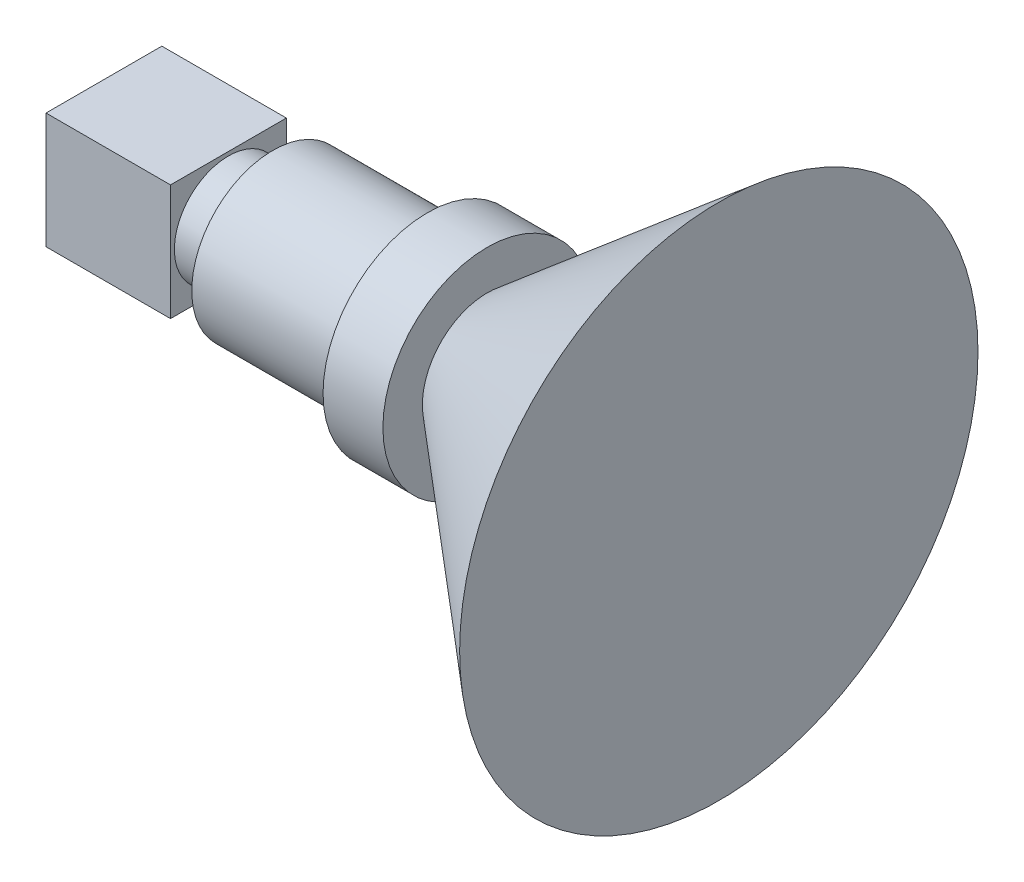
SolidWorks part; units mm, degrees
ref_plane "Front Plane" through (0, 0, 0) normal (0, 0, 1) x (1, 0, 0)
ref_plane "Top Plane" through (0, 0, 0) normal (0, 1, 0) x (1, 0, 0)
ref_plane "Right Plane" through (0, 0, 0) normal (1, 0, 0) x (0, 0, -1)
sketch "Sketch2" plane through (0, 0, 0) normal (0, 1, 0) x (1, 0, 0)
  line L1 (-16.125, -15) -> (16.125, -15)
  line L2 (-16.125, -15) -> (-16.125, 15)
  line L3 (-16.125, 15) -> (16.125, 15)
  line L4 (16.125, -15) -> (16.125, 15)
  line L5 (-16.125, -15) -> (16.125, 15) construction
  line L6 (-16.125, 15) -> (16.125, -15) construction
  point P0 (0, 0)
  dimension "D1" = 32.25
  dimension "D2" = 30
extrude "Boss-Extrude1" add sketch "Sketch2" along normal mid plane 30
sketch "Sketch4" plane through (16.125, 0, 0) normal (1, 0, 0) x (0, 0, -1)
  circle A0 centre (0, 0) radius 14
  dimension "D1" = 28
extrude "Boss-Extrude2" add sketch "Sketch4" along normal blind 11.5
sketch "Sketch5" plane through (27.625, 0, 0) normal (1, 0, 0) x (0, 0, -1)
  circle A0 centre (0, 0) radius 21
  dimension "D1" = 42
extrude "Boss-Extrude3" add sketch "Sketch5" along normal blind 40
sketch "Sketch6" plane through (67.625, 0, 0) normal (1, 0, 0) x (0, 0, -1)
  circle A0 centre (0, 0) radius 27
  dimension "D1" = 54
extrude "Boss-Extrude4" add sketch "Sketch6" along normal blind 15.5
sketch "Sketch12" plane through (0, 0, 0) normal (0, 0, 1) x (1, 0, 0)
  line L0 (63.125, 0) -> (143.125, 67.128)
  line L2 (143.125, 67.128) -> (143.125, -67.128) construction
  line L3 (143.125, -67.128) -> (63.125, 0) construction
  line L4 (63.125, 0) -> (143.125, 0) construction
  line L5 (83.125, -27) -> (83.125, 27) construction
  line L6 (63.125, 0) -> (143.125, 0)
  line L7 (143.125, 0) -> (143.125, 67.128)
  dimension "D1" = 80
  dimension "D2" = 20
  dimension "D3" = 80
revolve "Revolve1" add sketch "Sketch12" angle 360 about L6
sketch "Sketch13" plane through (0, -15, 0) normal (0, -1, 0) x (1, 0, 0)
  line L0 (-16.125, 0) -> (-12.125, 0) construction
  line L1 (-16.125, -15) -> (-16.125, 15) construction
  dimension "D1" = 4
hole_wizard "Tap Drill for 1/4-20 Tap1" positions "Sketch14" profile "Sketch15" hole size "1/4-20" standard "ANSI Inch"
sketch "Sketch14" plane through (0, -15, 0) normal (0, -1, 0) x (-1, 0, 0)
  point P0 (12.125, 0)
sketch "Sketch15" plane through (-12.125, -15, 0) normal (1, 0, 0) x (0, 0, -1)
  line L0 (0, 0) -> (0, 6.2938)
  line L1 (0, 6.2938) -> (2.5527, 4.76)
  line L2 (2.5527, 4.76) -> (2.5527, 0)
  line L5 (2.5527, 0) -> (0, 0)
  line L10 (0, 6.2938) -> (-2.5527, 4.76) construction
  line L11 (0, -6.35) -> (0, 107.95) construction
  dimension "Hole Dia." = 5.1054
  dimension "Hole Depth" = 4.76
  dimension "Drill Angle" = 118
